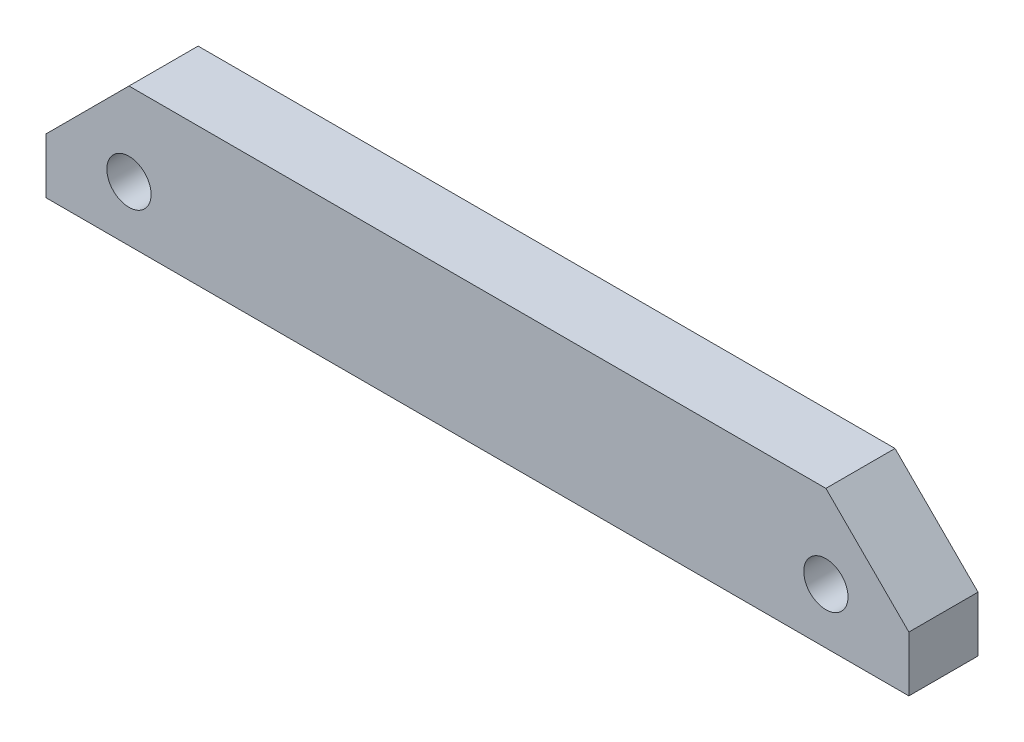
SolidWorks part; units mm, degrees
material "ABS"
ref_plane "Płaszczyzna przednia" through (0, 0, 0) normal (0, 0, 1) x (1, 0, 0)
ref_plane "Płaszczyzna górna" through (0, 0, 0) normal (0, 1, 0) x (1, 0, 0)
ref_plane "Płaszczyzna prawa" through (0, 0, 0) normal (1, 0, 0) x (0, 0, -1)
sketch "Szkic1" plane through (0, 0, 0) normal (0, 0, 1) x (1, 0, 0)
  line L0 (-31.2, 0) -> (31.2, 0)
  line L1 (-31.2, 0) -> (-31.2, 4)
  line L2 (-31.2, 4) -> (-25.2, 10)
  line L3 (31.2, 0) -> (31.2, 4)
  line L4 (31.2, 4) -> (25.2, 10)
  line L5 (25.2, 10) -> (-25.2, 10)
  point P4 (0, 0)
  dimension "D1" = 62.4
  dimension "D2" = 4
  dimension "D3" = 4
  dimension "D4" = 10
  dimension "D5" = 45
extrude "Dodanie-wyciągnięcie1" add sketch "Szkic1" along normal blind 5
sketch "Szkic2" plane through (0, 0, 5) normal (0, 0, 1) x (1, 0, 0)
  line L0 (-31.2, 0) -> (-25.2, 0) construction
  line L1 (-31.2, 0) -> (31.2, 0) construction
  line L2 (-25.2, 0) -> (-25.2, 4) construction
  line L3 (0, 0) -> (0, 10) construction
  line L4 (25.2, 10) -> (-25.2, 10) construction
  circle A0 centre (-25.2, 4) radius 1.6
  circle A1 centre (25.2, 4) radius 1.6
  dimension "D1" = 3.2
  dimension "D2" = 6
  dimension "D3" = 4
extrude "Wytnij-wyciągnięcie1" cut sketch "Szkic2" against normal through all
equation "\"Width\"=10"
equation "\"D2@Szkic2\"=\"Width\"/2+1"
equation "\"D3@Szkic2\"=\"Width\"/2-1"
